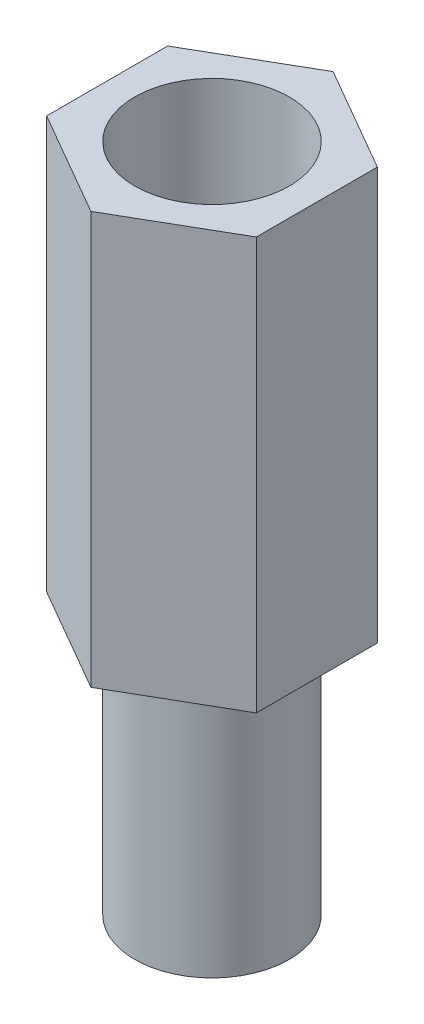
SolidWorks part; units mm, degrees
material "铜"
ref_plane "前视基准面" through (0, 0, 0) normal (0, 0, 1) x (1, 0, 0)
ref_plane "上视基准面" through (0, 0, 0) normal (0, 1, 0) x (1, 0, 0)
ref_plane "右视基准面" through (0, 0, 0) normal (1, 0, 0) x (0, 0, -1)
sketch "草图1" plane through (0, 0, 0) normal (0, 1, 0) x (1, 0, 0)
  line L1 (0, 2.35) -> (-2.0352, 1.175)
  line L2 (-2.0352, 1.175) -> (-2.0352, -1.175)
  line L3 (-2.0352, -1.175) -> (0, -2.35)
  line L4 (0, -2.35) -> (2.0352, -1.175)
  line L5 (2.0352, -1.175) -> (2.0352, 1.175)
  line L6 (2.0352, 1.175) -> (0, 2.35)
  circle A0 centre (0, 0) radius 2.0352 construction
  dimension "D1" = 4.7
extrude "凸台-拉伸1" add sketch "草图1" along normal blind 8
sketch "草图2" plane through (0, 8, 0) normal (0, 1, 0) x (1, 0, 0)
  circle A0 centre (0, 0) radius 1.5
  dimension "D1" = 3
extrude "切除-拉伸1" cut sketch "草图2" against normal blind 3
sketch "草图3" plane through (0, 0, 0) normal (0, -1, 0) x (1, 0, 0)
  circle A0 centre (0, 0) radius 1.5
  dimension "D1" = 3
extrude "凸台-拉伸2" add sketch "草图3" along normal blind 5
